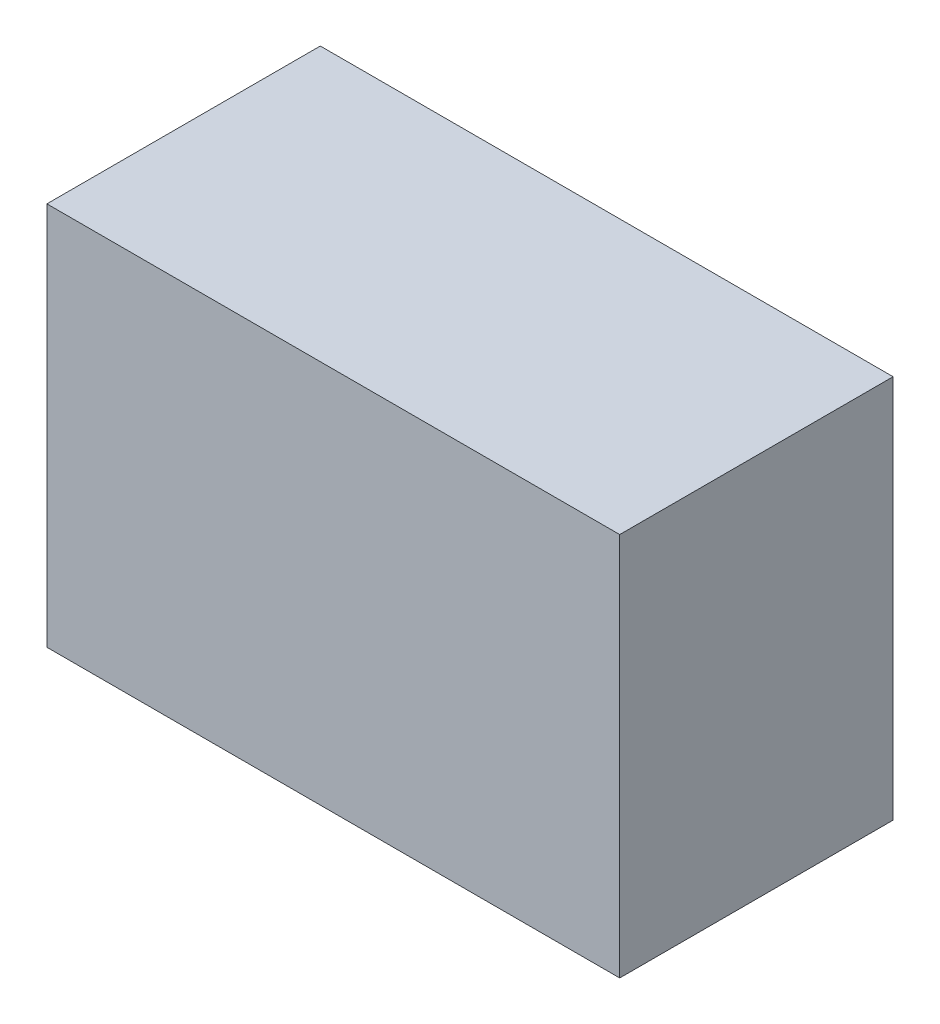
SolidWorks part; units mm, degrees
ref_plane "Front" through (0, 0, 0) normal (0, 0, 1) x (1, 0, 0)
ref_plane "Top" through (0, 0, 0) normal (0, 1, 0) x (1, 0, 0)
ref_plane "Right" through (0, 0, 0) normal (1, 0, 0) x (0, 0, -1)
sketch "Esquisse1" plane through (0, 0, 0) normal (0, 1, 0) x (1, 0, 0)
  line L1 (-220, 95) -> (220, 95)
  line L2 (-220, 95) -> (-220, -115)
  line L3 (-220, -115) -> (220, -115)
  line L4 (220, 95) -> (220, -115)
  point P4 (0, 95)
  dimension "D1" = 95
  dimension "D2" = 210
  dimension "D3" = 440
extrude "Boss.-Extru.1" add sketch "Esquisse1" along normal blind 295
